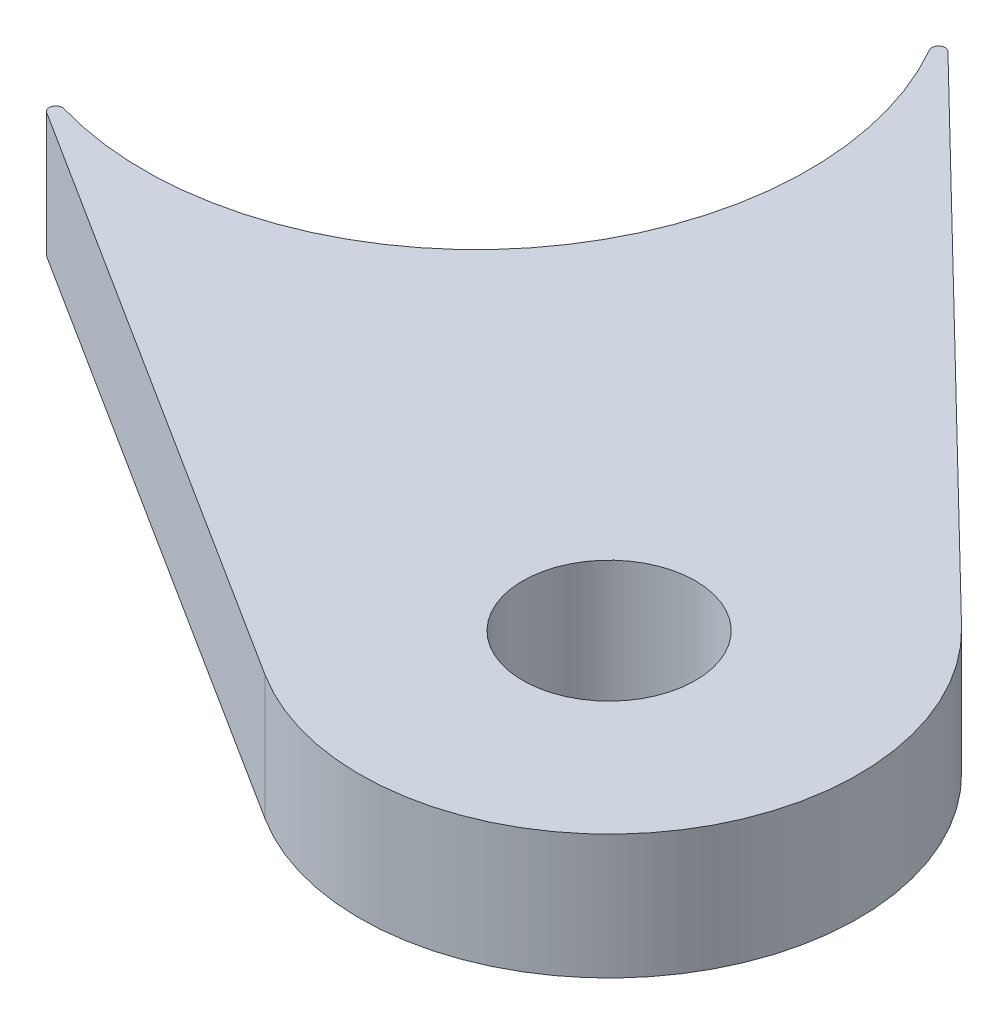
SolidWorks part; units mm, degrees
material "AISI 4130 Steel, annealed at 865C"
ref_plane "X-Y Datum" through (0, 0, 0) normal (0, 0, 1) x (1, 0, 0)
ref_plane "X-Z Datum" through (0, 0, 0) normal (0, 1, 0) x (1, 0, 0)
ref_plane "Y-Z Datum" through (0, 0, 0) normal (1, 0, 0) x (0, 0, -1)
sketch "Sketch1" plane through (0, 0, 0) normal (0, 1, 0) x (1, 0, 0)
  line L0 (20.2951, -4.286) -> (-1.6207, 17.0395)
  line L1 (8.554, -19.1581) -> (-17.2755, -2.7899)
  circle A0 centre (13.6525, -11.1125) radius 3.3
  circle A1 centre (13.6525, -11.1125) radius 9.525 construction
  circle A2 centre (-10.4775, 7.9375) radius 12.7 construction
  arc A3 (20.2951, -4.286) -> (8.554, -19.1581) centre (13.6525, -11.1125) cw
  arc A4 (-17.2755, -2.7899) -> (-1.6207, 17.0395) centre (-10.4775, 7.9375) ccw
  point P0 (-10.4775, 7.9375)
  dimension "D5" = 25.4
  dimension "D6" = 19.05
  dimension "D7" = 6.6
  dimension "D1" = 10.4775
  dimension "D2" = 7.9375
  dimension "D3" = 11.1125
  dimension "D4" = 13.6525
extrude "Boss-Extrude1" add sketch "Sketch1" along normal blind 4.7625
fillet "Fillet1" radius 0.254 2 edges at (-17.2755, 2.3813, 2.7899) (-1.6207, 2.3813, -17.0395)
